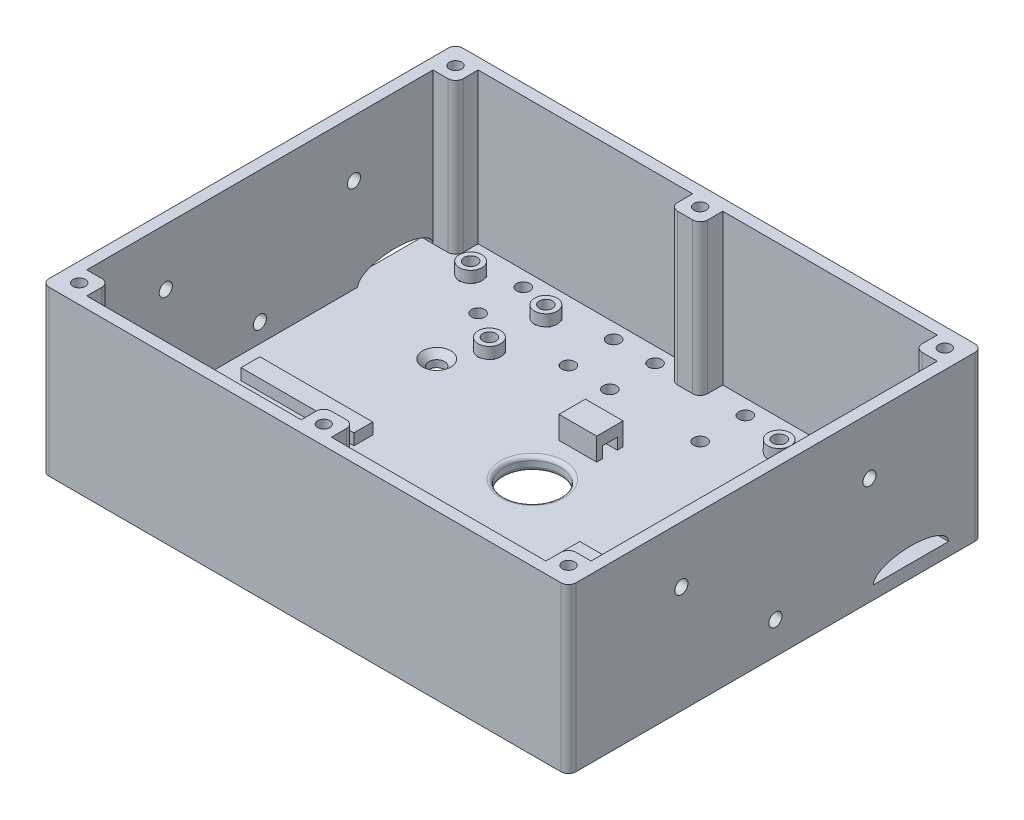
SolidWorks part; units mm, degrees
ref_plane "Front Plane" through (0, 0, 0) normal (0, 0, 1) x (1, 0, 0)
ref_plane "Top Plane" through (0, 0, 0) normal (0, 1, 0) x (1, 0, 0)
ref_plane "Right Plane" through (0, 0, 0) normal (1, 0, 0) x (0, 0, -1)
sketch "Sketch1" plane through (0, 0, 0) normal (0, 1, 0) x (1, 0, 0)
  line L1 (70, -55) -> (-70, -55)
  line L2 (70, -55) -> (70, 55)
  line L3 (70, 55) -> (-70, 55)
  line L4 (-70, -55) -> (-70, 55)
  line L5 (70, -55) -> (-70, 55) construction
  line L6 (70, 55) -> (-70, -55) construction
  point P0 (0, 0)
  dimension "D1" = 110
  dimension "D2" = 140
extrude "Bottom" add sketch "Sketch1" along normal blind 3.5
sketch "Sketch3" plane through (0, 3.5, 0) normal (0, 1, 0) x (1, 0, 0)
  line L0 (-70, 55) -> (70, 55)
  line L1 (70, 55) -> (70, -55)
  line L2 (70, -55) -> (-70, -55)
  line L3 (-70, -55) -> (-70, 55)
  line L4 (-61, 52) -> (-4, 52)
  line L5 (67, 46) -> (67, -46)
  line L6 (61, -52) -> (4, -52)
  line L7 (0, 55) -> (0, -55) construction
  line L8 (-67, 46) -> (-61, 46)
  line L9 (-61, 46) -> (-61, 52)
  line L10 (61, 52) -> (61, 46)
  line L11 (61, 46) -> (67, 46)
  line L12 (67, -46) -> (61, -46)
  line L13 (61, -46) -> (61, -52)
  line L14 (-67, -46) -> (-61, -46)
  line L15 (-61, -46) -> (-61, -52)
  line L16 (-67, -46) -> (-67, 46)
  line L17 (0, 0) -> (67, 0) construction
  line L18 (4, -52) -> (4, -46)
  line L19 (-4, 52) -> (-4, 46)
  line L20 (-4, 46) -> (4, 46)
  line L21 (4, 52) -> (4, 46)
  line L22 (0, 46) -> (0, 42.7097) construction
  line L23 (4, 52) -> (61, 52)
  line L24 (-4, -46) -> (4, -46)
  line L25 (-4, -52) -> (-4, -46)
  line L26 (-4, -52) -> (-61, -52)
  dimension "D1" = 3
  dimension "D2" = 3
  dimension "D3" = 3
  dimension "D4" = 3
  dimension "D5" = 6
  dimension "D6" = 8
extrude "Wall" add sketch "Sketch3" along normal blind 40
sketch "Sketch4" plane through (0, 43.5, 0) normal (0, 1, 0) x (1, 0, 0)
  line L0 (-70, 55) -> (-70, -55) construction
  line L1 (70, 55) -> (-70, 55) construction
  line L2 (70, -55) -> (70, 55) construction
  line L3 (-70, -55) -> (70, -55) construction
  line L4 (0, 55) -> (0, 30.3541) construction
  line L5 (70, 0) -> (33.8613, 0) construction
  circle A0 centre (-65, 50) radius 1.625
  circle A1 centre (65, 50) radius 1.625
  circle A2 centre (65, -50) radius 1.625
  circle A3 centre (-65, -50) radius 1.625
  circle A4 centre (0, 50) radius 1.625
  circle A5 centre (0, -50) radius 1.625
  dimension "D1" = 3.25
  dimension "D4" = 5
  dimension "D2" = 5
  dimension "D3" = 5
  dimension "D5" = 5
extrude "Top Plate Screw Holes" cut sketch "Sketch4" against normal blind 30 draft 1
fillet "Fillet14" radius 2 1 edges at (-4, 23.5, 46)
fillet "Fillet13" radius 2 1 edges at (4, 23.5, 46)
fillet "Fillet12" radius 2 1 edges at (-4, 23.5, -46)
fillet "Fillet11" radius 2 1 edges at (4, 23.5, -46)
fillet "Fillet1" radius 2 1 edges at (-61, 23.5, 46)
fillet "Fillet2" radius 2 1 edges at (61, 23.5, 46)
fillet "Fillet3" radius 2 1 edges at (61, 23.5, -46)
fillet "Fillet4" radius 2 1 edges at (-61, 23.5, -46)
fillet "Fillet5" radius 2 1 edges at (-70, 21.75, -55)
fillet "Fillet6" radius 2 1 edges at (70, 21.75, -55)
fillet "Fillet7" radius 2 1 edges at (70, 21.75, 55)
fillet "Fillet8" radius 2 1 edges at (-70, 21.75, 55)
sketch "M4 Mount" plane through (0, 3.5, 0) normal (0, -1, 0) x (1, 0, 0)
  line L0 (70, 53) -> (70, -53) construction
  line L1 (0, 0) -> (23.8675, 0) construction
  line L2 (0, 0) -> (0, -19.9393) construction
  circle A0 centre (40, -20) radius 2.1
  circle A1 centre (40, 20) radius 2.1
  circle A2 centre (-40, 20) radius 2.1
  circle A3 centre (-40, -20) radius 2.1
  dimension "D1" = 4.2
  dimension "D2" = 30
  dimension "D3" = 20
  dimension "D4" = 20
extrude "M4 Mount Cut" cut sketch "M4 Mount" along normal through all
sketch "M4 Screw Heads" plane through (0, 3.5, 0) normal (0, 1, 0) x (1, 0, 0)
  circle A0 centre (40, -20) radius 3.75
  circle A1 centre (40, 20) radius 3.75
  circle A2 centre (-40, 20) radius 3.75
  circle A3 centre (-40, -20) radius 3.75
  dimension "D1" = 7.5
extrude "Cut-Extrude3" cut sketch "M4 Screw Heads" against normal blind 10 draft 45
sketch "Sketch7" plane through (0, 0, 0) normal (0, -1, 0) x (1, 0, 0)
  line L0 (68, -55) -> (-68, -55) construction
  line L2 (0, -55) -> (0.5731, 13.4899) construction
  circle A0 centre (0.4184, -5) radius 7.5
  dimension "D1" = 15
  dimension "D2" = 50
extrude "USB Cabel Cut" cut sketch "Sketch7" against normal through all
fillet "Fillet9" radius 1 1 edges at (0.4184, 0, -12.5)
fillet "Fillet10" radius 1 1 edges at (0.4184, 3.5, 2.5)
sketch "Sketch8" plane through (0, 3.5, 0) normal (0, 1, 0) x (1, 0, 0)
  line L0 (0, 46) -> (0, 22.3123) construction
  line L1 (2, 46) -> (-2, 46) construction
  line L2 (-4, 52) -> (-61, 52) construction
  line L3 (-35, 52) -> (-35, 37.9688) construction
  circle A0 centre (-10, 48) radius 1.75
  circle A1 centre (-10, 36) radius 1.75
  circle A2 centre (14, 48) radius 1.75
  circle A3 centre (14, 36) radius 1.75
  circle A4 centre (-45, 48) radius 1.75
  circle A5 centre (-45, 36) radius 1.75
  circle A6 centre (-21, 48) radius 1.75
  circle A7 centre (-21, 36) radius 1.75
  dimension "D1" = 3.5
  dimension "D5" = 14
  dimension "D2" = 12
  dimension "D3" = 10
  dimension "D4" = 4
  dimension "D6" = 35
  dimension "D8" = 10
  dimension "D9" = 14
extrude "UV LAMP M3 CUT" cut sketch "Sketch8" against normal blind 10
sketch "M3 Connection" plane through (-67, 0, 0) normal (1, 0, 0) x (0, 0, -1)
  line L0 (46, 23.5) -> (13.1188, 23.5) construction
  line L1 (46, 43.5) -> (46, 3.5) construction
  line L2 (0, 3.5) -> (0, 17.9528) construction
  line L3 (46, 3.5) -> (-46, 3.5) construction
  circle A0 centre (25, 28.5) radius 1.75
  circle A1 centre (0, 8.5) radius 1.75
  circle A2 centre (-25, 28.5) radius 1.75
  dimension "D1" = 3.5
  dimension "D2" = 5
  dimension "D3" = 15
  dimension "D4" = 25
sketch "Cable Pass" plane through (-67, 0, 0) normal (1, 0, 0) x (0, 0, -1)
  line L0 (46, 3.5) -> (-46, 3.5) construction
  line L1 (46, 3.5) -> (26, 3.5)
  ellipse E0 centre (36, 3.5) end of major axis (46, 3.5) minor radius 4 (46, 3.5) -> (26, 3.5) ccw
  dimension "D1" = 20
  dimension "D2" = 4
sketch "Sketch12" plane through (67, 0, 0) normal (-1, 0, 0) x (0, 0, 1)
  line L0 (-26, 3.5) -> (-46, 3.5)
  line L1 (46, 3.5) -> (-46, 3.5) construction
  ellipse E0 centre (-36, 3.5) end of major axis (-26, 3.5) minor radius 4 (-26, 3.5) -> (-46, 3.5) ccw
  dimension "D1" = 20
  dimension "D2" = 4
extrude "M3 Connection CUT" cut sketch "M3 Connection" against normal blind 10 and the other way up to surface other way up to face at (70, 21.75, 0)
extrude "Cable Pass CUT" cut sketch "Cable Pass" against normal blind 10
extrude "Cut-Extrude4" cut sketch "Sketch12" against normal blind 10
sketch "Sketch9" plane through (0, 3.5, 0) normal (0, 1, 0) x (1, 0, 0)
  line L0 (67, -46) -> (67, 26) construction
  line L1 (-4, 52) -> (-61, 52) construction
  line L2 (-55, 44) -> (-35, 44) construction
  line L3 (-45, 44) -> (-45, 45.6151) construction
  line L4 (-45, 49.75) -> (-45, 46.25) construction
  line L5 (-61, 52) -> (-61, 48) construction
  line L7 (0, 46) -> (0, 18.189) construction
  line L8 (2, 46) -> (-2, 46) construction
  line L9 (-61, -6) -> (-31, -6)
  line L10 (-61, -6) -> (-61, -11)
  line L11 (-61, -11) -> (-31, -11)
  line L12 (-31, -6) -> (-31, -11)
  line L13 (24, -6) -> (24, -11)
  line L14 (54, -11) -> (24, -11)
  line L15 (54, -6) -> (24, -6)
  line L16 (54, -6) -> (54, -11)
  circle A0 centre (47, 44) radius 3
  circle A1 centre (27, 44) radius 3
  circle A2 centre (47, 29) radius 3
  circle A3 centre (-35, 44) radius 3
  circle A4 centre (-35, 29) radius 3
  circle A5 centre (-55, 44) radius 3
  circle A6 centre (-45, 48) radius 1.75 construction
  dimension "D1" = 6
  dimension "D2" = 15
  dimension "D3" = 20
  dimension "D4" = 20
  dimension "D5" = 20
  dimension "D6" = 8
  dimension "D9" = 50
  dimension "D10" = 30
  dimension "D11" = 5
  dimension "D12" = 13
  dimension "D13" = 30
extrude "Curcuit Board Mount Posts EXT" add sketch "Sketch9" along normal blind 3
sketch "Sketch10" plane through (0, 6.5, 0) normal (0, 1, 0) x (1, 0, 0)
  circle A0 centre (-55, 44) radius 1.75
  circle A1 centre (-35, 44) radius 1.75
  circle A2 centre (-35, 29) radius 1.75
  circle A3 centre (27, 44) radius 1.75
  circle A4 centre (47, 44) radius 1.75
  circle A5 centre (47, 29) radius 1.75
  dimension "D1" = 3.5
extrude "M3 Screw Curcuit Mount CUT" cut sketch "Sketch10" against normal through all
sketch "Sketch11" plane through (0, 0, 0) normal (0, -1, 0) x (1, 0, 0)
  line L1 (-35, -47.1754) -> (-32.25, -45.5877)
  line L2 (-32.25, -45.5877) -> (-32.25, -42.4123)
  line L3 (-32.25, -42.4123) -> (-35, -40.8246)
  line L4 (-35, -40.8246) -> (-37.75, -42.4123)
  line L5 (-37.75, -42.4123) -> (-37.75, -45.5877)
  line L6 (-37.75, -45.5877) -> (-35, -47.1754)
  line L7 (-55, -47.1754) -> (-52.25, -45.5877)
  line L8 (-52.25, -45.5877) -> (-52.25, -42.4123)
  line L9 (-52.25, -42.4123) -> (-55, -40.8246)
  line L10 (-55, -40.8246) -> (-57.75, -42.4123)
  line L11 (-57.75, -42.4123) -> (-57.75, -45.5877)
  line L12 (-57.75, -45.5877) -> (-55, -47.1754)
  line L13 (-35, -32.1754) -> (-32.25, -30.5877)
  line L14 (-32.25, -30.5877) -> (-32.25, -27.4123)
  line L15 (-32.25, -27.4123) -> (-35, -25.8246)
  line L16 (-35, -25.8246) -> (-37.75, -27.4123)
  line L17 (-37.75, -27.4123) -> (-37.75, -30.5877)
  line L18 (-37.75, -30.5877) -> (-35, -32.1754)
  line L19 (27, -47.1754) -> (29.75, -45.5877)
  line L20 (29.75, -45.5877) -> (29.75, -42.4123)
  line L21 (29.75, -42.4123) -> (27, -40.8246)
  line L22 (27, -40.8246) -> (24.25, -42.4123)
  line L23 (24.25, -42.4123) -> (24.25, -45.5877)
  line L24 (24.25, -45.5877) -> (27, -47.1754)
  line L25 (47, -47.1754) -> (49.75, -45.5877)
  line L26 (49.75, -45.5877) -> (49.75, -42.4123)
  line L27 (49.75, -42.4123) -> (47, -40.8246)
  line L28 (47, -40.8246) -> (44.25, -42.4123)
  line L29 (44.25, -42.4123) -> (44.25, -45.5877)
  line L30 (44.25, -45.5877) -> (47, -47.1754)
  line L31 (47, -32.1754) -> (49.75, -30.5877)
  line L32 (49.75, -30.5877) -> (49.75, -27.4123)
  line L33 (49.75, -27.4123) -> (47, -25.8246)
  line L34 (47, -25.8246) -> (44.25, -27.4123)
  line L35 (44.25, -27.4123) -> (44.25, -30.5877)
  line L36 (44.25, -30.5877) -> (47, -32.1754)
  circle A0 centre (-35, -44) radius 2.75 construction
  circle A1 centre (-55, -44) radius 2.75 construction
  circle A2 centre (-35, -29) radius 2.75 construction
  circle A3 centre (27, -44) radius 2.75 construction
  circle A4 centre (47, -44) radius 2.75 construction
  circle A5 centre (47, -29) radius 2.75 construction
  circle A6 centre (47, -29) radius 1.75 construction
  dimension "D1" = 5.5
  dimension "D2" = 5.5
  dimension "D3" = 5.5
  dimension "D4" = 5.5
  dimension "D5" = 5.5
  dimension "D6" = 5.5
extrude "M3 Head Circuit Mount CUT" cut sketch "Sketch11" against normal blind 3.5
sketch "Sketch14" plane through (0, 3.5, 0) normal (0, 1, 0) x (1, 0, 0)
  line L0 (2, 46) -> (-2, 46) construction
  line L1 (5, 17.5) -> (-5, 17.5)
  line L2 (5, 17.5) -> (5, 24.5)
  line L3 (5, 24.5) -> (-5, 24.5)
  line L4 (-5, 17.5) -> (-5, 24.5)
  line L5 (5, 17.5) -> (-5, 24.5) construction
  line L6 (5, 24.5) -> (-5, 17.5) construction
  point P0 (0, 21)
  dimension "D1" = 7
  dimension "D2" = 10
  dimension "D3" = 25
extrude "Boss-Extrude1" add sketch "Sketch14" along normal blind 6
sketch "Sketch16" plane through (-5, 0, 0) normal (-1, 0, 0) x (0, 0, 1)
  line L0 (-24.5, 3.5) -> (-17.5, 3.5) construction
  line L1 (-23, 3.5) -> (-19, 3.5)
  line L2 (-23, 3.5) -> (-23, 6.5)
  line L3 (-23, 6.5) -> (-19, 6.5)
  line L4 (-19, 3.5) -> (-19, 6.5)
  line L5 (-21, 3.5) -> (-21, 6.5) construction
  dimension "D1" = 4
  dimension "D3" = 3
extrude "Cut-Extrude6" cut sketch "Sketch16" against normal up to surface (10 mm away) up to face at (5, 6.5, -21)
sketch "Sketch18" plane through (0, 0, -55) normal (0, 0, -1) x (-1, 0, 0)
  circle A0 centre (-37.4229, 25.697) radius 6.2463
  circle A1 centre (36.9622, 25.697) radius 8.681
  dimension "D1" = 12.4927
equation "\"BOXWALL\"=3"
equation "\"D2@Sketch3\"= \"BOXWALL\""
equation "\"D3@Sketch3\"=\"BOXWALL\""
equation "\"D4@Sketch3\"=\"BOXWALL\""
equation "\"SCREW_M3\"=3.5"
equation "\"D1@Sketch8\"=\"SCREW_M3\""
equation "\"D1@M3 Connection\"=\"SCREW_M3\""
equation "\"D1@Sketch10\"=\"SCREW_M3\""
equation "\"SCREW_M3_HEAD\"=5.5"
equation "\"D1@Sketch11\"=\"SCREW_M3_HEAD\""
equation "\"D2@Sketch11\"=\"SCREW_M3_HEAD\""
equation "\"D3@Sketch11\"=\"SCREW_M3_HEAD\""
equation "\"D4@Sketch11\"=\"SCREW_M3_HEAD\""
equation "\"D5@Sketch11\"=\"SCREW_M3_HEAD\""
equation "\"D6@Sketch11\"=\"SCREW_M3_HEAD\""
